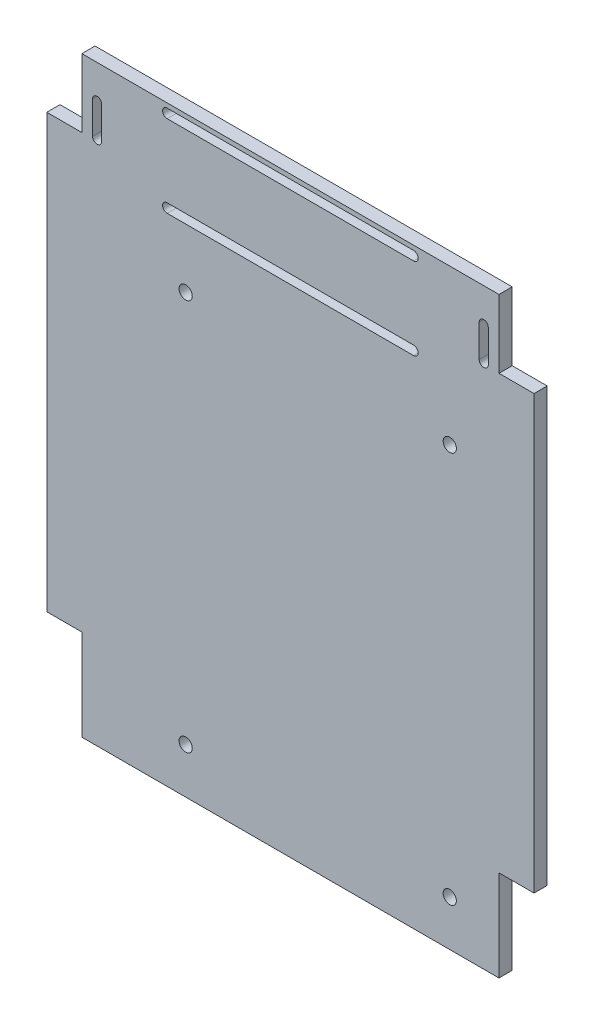
SolidWorks part; units mm, degrees
ref_plane "Front Plane" through (0, 0, 0) normal (0, 0, 1) x (1, 0, 0)
ref_plane "Top Plane" through (0, 0, 0) normal (0, 1, 0) x (1, 0, 0)
ref_plane "Right Plane" through (0, 0, 0) normal (1, 0, 0) x (0, 0, -1)
sketch "Sketch1" plane through (0, 0, 0) normal (0, 0, 1) x (1, 0, 0)
  line L4 (0, -57.4087) -> (0, 73.1354) construction
  line L5 (-53.5, -47.5) -> (-45.8, -47.5)
  line L6 (-53.5, -47.5) -> (-53.5, 47.5)
  line L7 (-53.5, 47.5) -> (-45.8, 47.5)
  line L8 (53.5, -47.5) -> (53.5, 47.5)
  line L9 (-53.5, -47.5) -> (53.5, 47.5) construction
  line L10 (-53.5, 47.5) -> (53.5, -47.5) construction
  line L11 (0, 0) -> (92.3064, 0) construction
  line L12 (-23, -57.5) -> (35, -57.5) construction
  line L13 (6, -57.5) -> (6, -50.4105) construction
  line L14 (-27.0639, 60.5) -> (27.0639, 60.5) construction
  line L15 (-27.0639, 61.5) -> (27.0639, 61.5)
  line L20 (-27.0639, 59.5) -> (27.0639, 59.5)
  line L21 (0, 51.5) -> (15.2483, 51.5) construction
  line L22 (-27.0639, 42.5) -> (27.0639, 42.5) construction
  line L23 (-27.0639, 41.5) -> (27.0639, 41.5)
  line L24 (45.8039, 47.5) -> (53.5, 47.5)
  line L26 (45.8039, 47.5) -> (45.8039, 62.5)
  line L27 (45.8039, 62.5) -> (-45.8, 62.5)
  line L28 (-45.8, 47.5) -> (-45.8, 62.5)
  line L29 (-27.0639, 43.5) -> (27.0639, 43.5)
  line L30 (-42.4566, 55.059) -> (-42.4566, 47.941) construction
  line L31 (-45.8, -47.5) -> (-45.8, -67.5)
  line L32 (-45.8, -67.5) -> (45.8, -67.5)
  line L33 (45.8, -67.5) -> (45.8, -47.5)
  line L34 (45.8, -47.5) -> (53.5, -47.5)
  line L35 (-41.4566, 55.059) -> (-41.4566, 47.941)
  line L36 (-43.4566, 55.059) -> (-43.4566, 47.941)
  line L37 (42.4566, 55.059) -> (42.4566, 47.941) construction
  line L38 (41.4566, 55.059) -> (41.4566, 47.941)
  line L39 (43.4566, 55.059) -> (43.4566, 47.941)
  circle A0 centre (35, -57.5) radius 1.45
  circle A1 centre (35, 28.5) radius 1.45
  circle A2 centre (-23, -57.5) radius 1.45
  circle A3 centre (-23, 28.5) radius 1.45
  arc A4 (-27.0639, 61.5) -> (-27.0639, 59.5) centre (-27.0639, 60.5) ccw
  arc A5 (27.0639, 59.5) -> (27.0639, 61.5) centre (27.0639, 60.5) ccw
  arc A6 (-27.0639, 41.5) -> (-27.0639, 43.5) centre (-27.0639, 42.5) cw
  arc A7 (27.0639, 43.5) -> (27.0639, 41.5) centre (27.0639, 42.5) cw
  arc A8 (-41.4566, 55.059) -> (-43.4566, 55.059) centre (-42.4566, 55.059) ccw
  arc A9 (-43.4566, 47.941) -> (-41.4566, 47.941) centre (-42.4566, 47.941) ccw
  arc A10 (41.4566, 55.059) -> (43.4566, 55.059) centre (42.4566, 55.059) cw
  arc A11 (43.4566, 47.941) -> (41.4566, 47.941) centre (42.4566, 47.941) cw
  point P0 (0, 0)
  point P10 (0, 60.5)
  point P31 (0, 42.5)
  point P46 (-42.4566, 51.5)
  point P51 (0, 0)
  point P52 (0, 0)
  point P55 (42.4566, 51.5)
  dimension "D3" = 6
  dimension "D10" = 2.9
  dimension "D11" = 2.9
  dimension "D13" = 2.9
  dimension "D14" = 2.9
  dimension "D1" = 107
  dimension "D2" = 95
  dimension "D4" = 10
  dimension "D5" = 2
  dimension "D6" = 2
  dimension "D7" = 9
  dimension "D8" = 2
  dimension "D9" = 86
  dimension "D12" = 58
  dimension "D15" = 58
  dimension "D17" = 15
  dimension "D18" = 7.7
  dimension "D19" = 7.6961
  dimension "D20" = 7.7
  dimension "D21" = 7.7
  dimension "D22" = 20
extrude "Boss-Extrude2" add sketch "Sketch1" along normal blind 2.9
